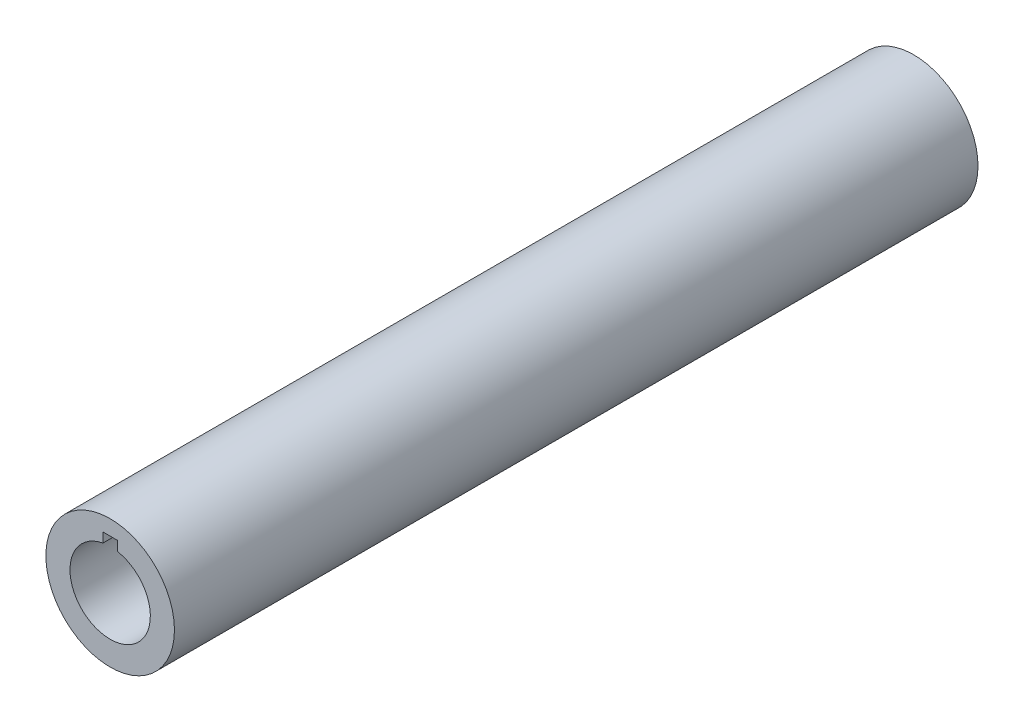
SolidWorks part; units mm, degrees
ref_plane "Alzado" through (0, 0, 0) normal (0, 0, 1) x (1, 0, 0)
ref_plane "Planta" through (0, 0, 0) normal (0, 1, 0) x (1, 0, 0)
ref_plane "Vista lateral" through (0, 0, 0) normal (1, 0, 0) x (0, 0, -1)
sketch "Croquis2" plane through (0, 0, 0) normal (0, 0, 1) x (1, 0, 0)
  line L0 (0, 0) -> (0, 2.5) construction
  line L2 (-0.45, 2.4592) -> (-0.45, 3.0592)
  line L3 (-0.45, 3.0592) -> (0.45, 3.0592)
  line L4 (0.45, 2.4592) -> (0.45, 3.0592)
  arc A0 (-0.45, 2.4592) -> (0.45, 2.4592) centre (0, 0) ccw
  circle A1 centre (0, 0) radius 4
  dimension "D1" = 5
  dimension "D4" = 8
  dimension "D2" = 0.9
  dimension "D3" = 0.6
extrude "Saliente-Extruir1" add sketch "Croquis2" along normal blind 50
